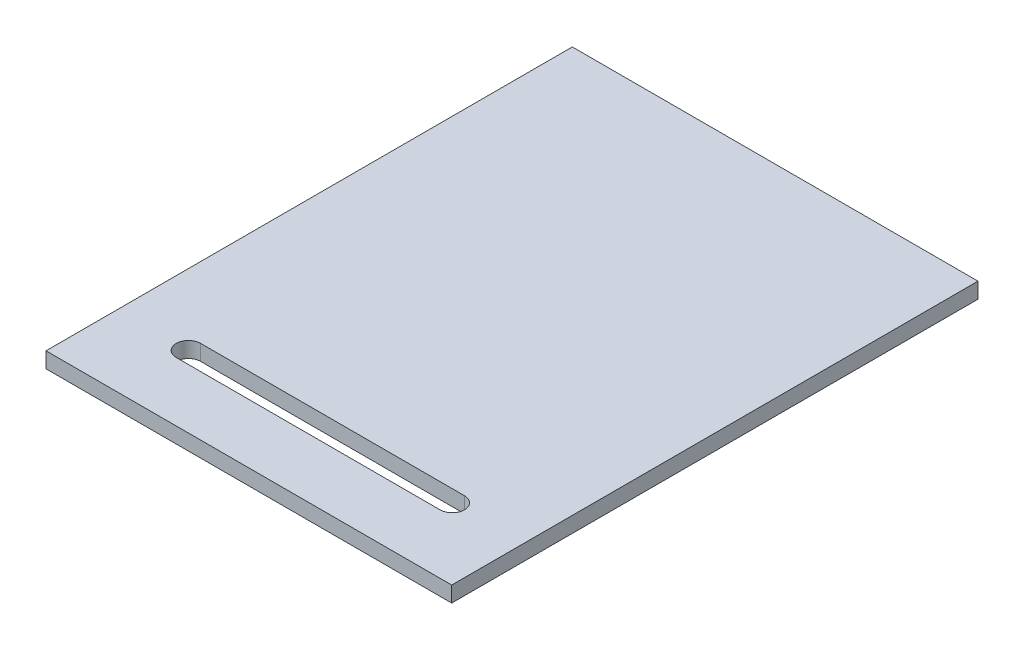
SolidWorks part; units mm, degrees
ref_plane "Ebene vorne" through (0, 0, 0) normal (0, 0, 1) x (1, 0, 0)
ref_plane "Ebene oben" through (0, 0, 0) normal (0, 1, 0) x (1, 0, 0)
ref_plane "Ebene rechts" through (0, 0, 0) normal (1, 0, 0) x (0, 0, -1)
sketch "Skizze1" plane through (0, 0, 0) normal (0, 1, 0) x (1, 0, 0)
  line L1 (-20.7586, 26.9302) -> (20.7586, 26.9302)
  line L2 (-20.7586, 26.9302) -> (-20.7586, -26.9302)
  line L3 (-20.7586, -26.9302) -> (20.7586, -26.9302)
  line L4 (20.7586, 26.9302) -> (20.7586, -26.9302)
  line L5 (-20.7586, 26.9302) -> (20.7586, -26.9302) construction
  line L6 (-20.7586, -26.9302) -> (20.7586, 26.9302) construction
  line L7 (-13.5, -18.361) -> (13.5, -18.361)
  line L8 (-2.5961, -18.361) -> (1.0466, -18.361) construction
  line L11 (13.5, -20.861) -> (-13.5, -20.861)
  line L12 (0, -18.361) -> (0, -20.861)
  arc A0 (13.5, -18.361) -> (13.5, -20.861) centre (13.5, -19.611) cw
  arc A1 (-13.5, -18.361) -> (-13.5, -20.861) centre (-13.5, -19.611) ccw
  point P0 (0, 0)
extrude "Aufsatz-Linear austragen1" add sketch "Skizze1" along normal blind 1.6 contours L4 L1 L2 L3 A1 L7 A0 L11
